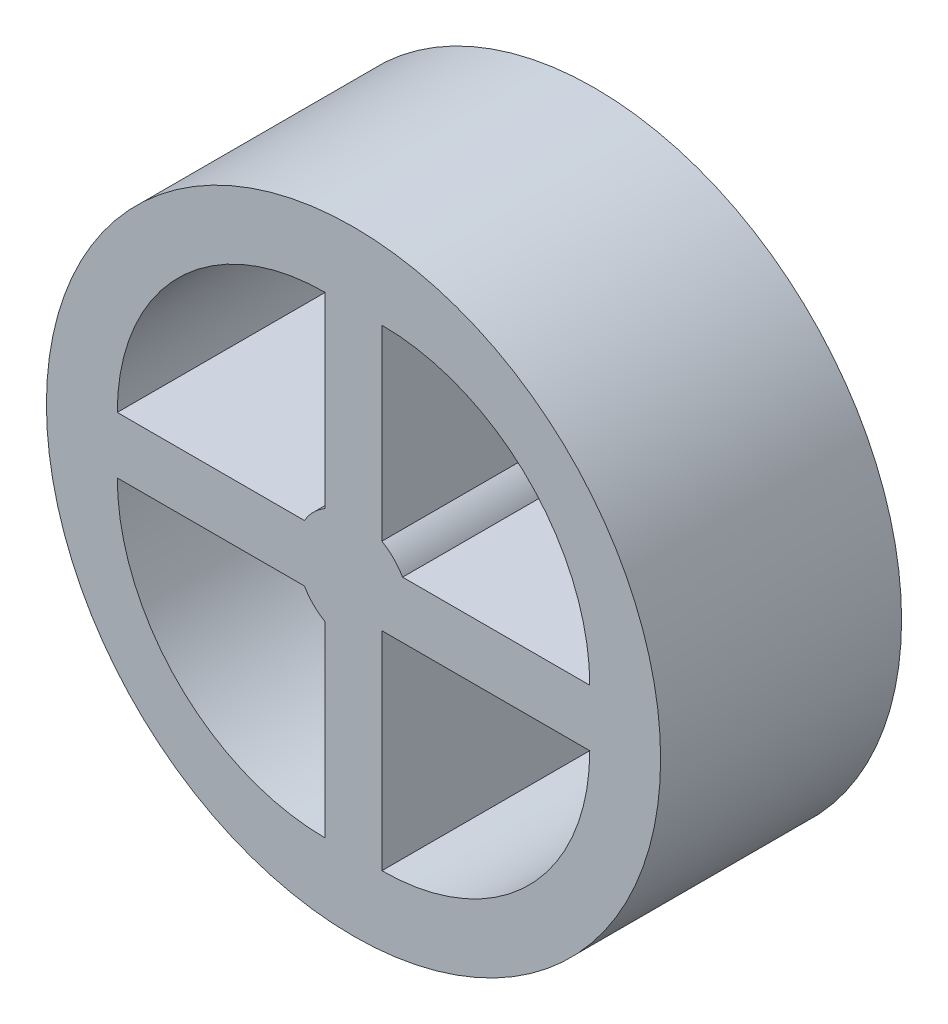
SolidWorks part; units mm, degrees
ref_plane "前视基准面" through (0, 0, 0) normal (0, 0, 1) x (1, 0, 0)
ref_plane "上视基准面" through (0, 0, 0) normal (0, 1, 0) x (1, 0, 0)
ref_plane "右视基准面" through (0, 0, 0) normal (1, 0, 0) x (0, 0, -1)
sketch "草图1" plane through (0, 0, 0) normal (0, 0, 1) x (1, 0, 0)
  circle A0 centre (0, 0) radius 325
  dimension "D1" = 650
extrude "凸台-拉伸1" add sketch "草图1" along normal blind 255
sketch "草图2" plane through (0, 0, 0) normal (0, 0, 1) x (1, 0, 0)
  line L1 (51.9615, 30) -> (250, 30)
  line L2 (30, 250) -> (30, 51.9615)
  arc A0 (51.9615, 30) -> (30, 51.9615) centre (0, 0) ccw
  arc A1 (30, 250) -> (250, 30) centre (30, 30) cw
  dimension "D1" = 120
  dimension "D2" = 30
  dimension "D3" = 30
  dimension "D4" = 220
extrude "切除-拉伸2" cut sketch "草图2" along normal blind 255
sketch "草图3" plane through (0, 0, 0) normal (0, 0, 1) x (1, 0, 0)
  line L1 (-30, 250) -> (-30, 51.9615)
  line L2 (-51.9615, 30) -> (-250, 30)
  arc A0 (-30, 51.9615) -> (-51.9615, 30) centre (0, 0) ccw
  arc A1 (-30, 250) -> (-250, 30) centre (-30, 30) ccw
  dimension "D1" = 120
  dimension "D2" = 30
  dimension "D4" = 220
extrude "切除-拉伸3" cut sketch "草图3" along normal blind 255
sketch "草图8" plane through (0, 0, 0) normal (0, 0, 1) x (1, 0, 0)
  line L0 (-51.9615, -30) -> (361.296, -30) construction
  line L1 (30, -30) -> (30, -250)
  line L2 (30, -5.323) -> (30, -357.9692) construction
  line L3 (250, 30) -> (250, -276.794) construction
  line L4 (-30, -250) -> (242.1947, -250) construction
  line L5 (30, -30) -> (250, -30)
  arc A0 (250, -30) -> (30, -250) centre (30, -30) cw
sketch "草图9" plane through (0, 0, 0) normal (0, 0, 1) x (1, 0, 0)
  line L0 (-30, 51.9615) -> (-30, -344.7812) construction
  line L1 (-323.6124, -30) -> (377.0487, -30) construction
  line L2 (-30, -51.9615) -> (-30, -250)
  line L3 (-250, -30) -> (-51.9615, -30)
  arc A0 (-51.9615, -30) -> (-30, -51.9615) centre (0, 0) ccw
  circle A1 centre (0, 0) radius 325 construction
  arc A2 (-30, -250) -> (-250, -30) centre (-30, -30) cw
  dimension "D1" = 120
  dimension "D2" = 30
  dimension "D3" = 220
extrude "切除-拉伸7" cut sketch "草图9" along normal blind 255
sketch "草图10" plane through (0, 0, 0) normal (0, 0, 1) x (1, 0, 0)
  line L0 (-75.8522, -30) -> (385.9147, -30) construction
  line L2 (30, 123.0935) -> (30, -353.3116) construction
  line L4 (30, -30) -> (250, -30)
  line L5 (30, -30) -> (30, -250)
  arc A0 (250, -30) -> (30, -250) centre (30, -30) cw
  dimension "D1" = 220
extrude "切除-拉伸8" cut sketch "草图10" along normal blind 255
extrude "切除-拉伸6" cut sketch "草图8" along normal blind 255
